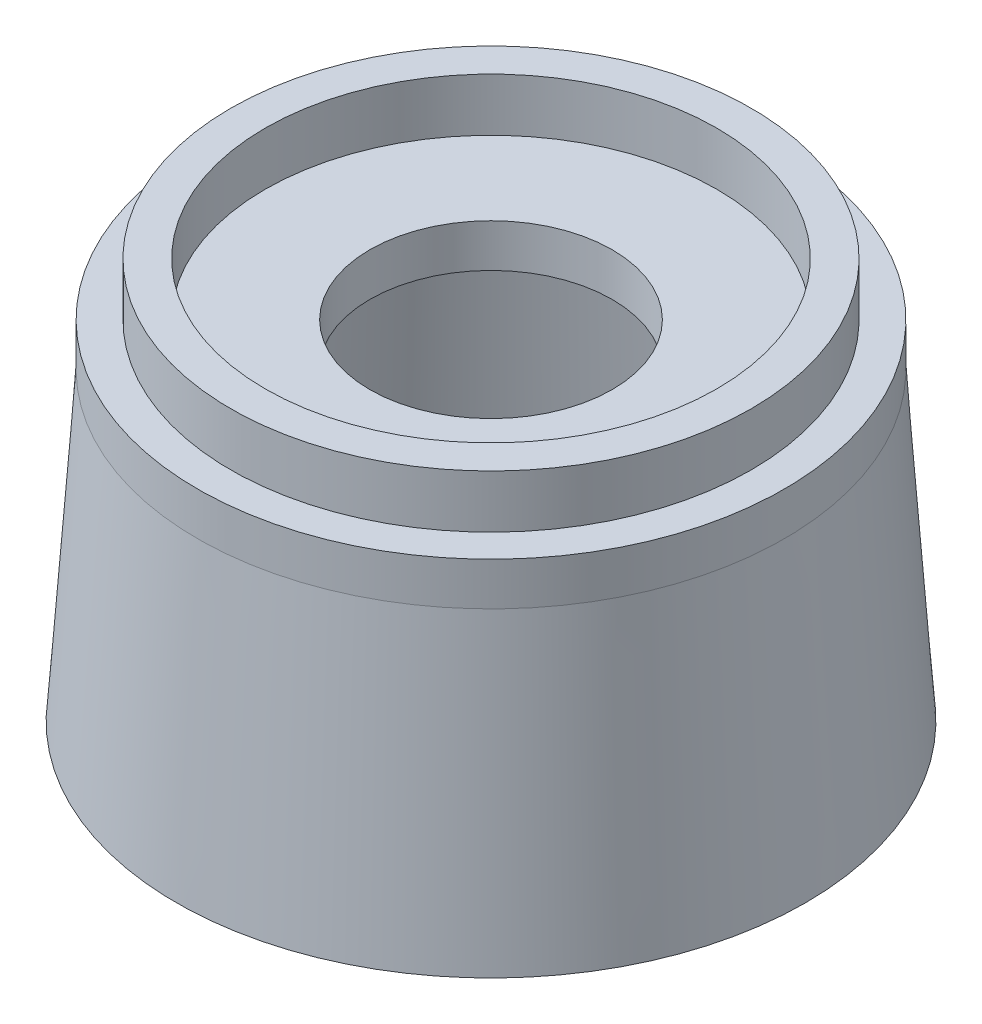
SolidWorks part; units mm, degrees
ref_plane "Plan de face" through (0, 0, 0) normal (0, 0, 1) x (1, 0, 0)
ref_plane "Plan de dessus" through (0, 0, 0) normal (0, 1, 0) x (1, 0, 0)
ref_plane "Plan de droite" through (0, 0, 0) normal (1, 0, 0) x (0, 0, -1)
sketch "Esquisse1" plane through (0, 0, 0) normal (0, 0, 1) x (1, 0, 0)
  line L0 (-11.4153, 52.3026) -> (-11.4153, -6.6974) construction
  line L1 (22.6847, 53.8026) -> (27.8847, 53.8026)
  line L2 (27.8847, 53.8026) -> (27.8847, 45.8026)
  line L3 (27.8847, 45.8026) -> (22.6847, 45.8026)
  line L4 (22.6847, 45.8026) -> (22.6847, 53.8026)
  line L5 (22.6847, 45.8026) -> (6.8847, 45.8026)
  line L6 (6.8847, 45.8026) -> (6.8847, 39.3026)
  line L7 (6.8847, 39.3026) -> (22.6847, 39.3026)
  line L8 (22.6847, 39.3026) -> (22.6847, 45.8026)
  line L9 (-11.4153, -6.6974) -> (36.0847, -6.6974) construction
  line L10 (22.6847, 45.8026) -> (32.8847, 45.8026)
  line L11 (22.6847, 45.8026) -> (22.6847, 39.3026)
  line L12 (22.6847, 39.3026) -> (32.8847, 39.3026)
  line L13 (32.8847, 45.8026) -> (32.8847, 39.3026)
  line L14 (32.8847, 39.3026) -> (36.0847, -6.6974)
  line L15 (29.8847, 39.3026) -> (33.3727, -6.6974)
  line L16 (36.0847, -6.6974) -> (33.3727, -6.6974)
  dimension "D1" = 59
  dimension "D2" = 39.3
  dimension "D3" = 8
  dimension "D4" = 21
  dimension "D5" = 5.2
  dimension "D6" = 15.8
  dimension "D7" = 6.5
  dimension "D8" = 26
  dimension "D9" = 47.5
  dimension "D10" = 46
  dimension "D11" = 3
revolve "Révolution1" add sketch "Esquisse1" angle 360 about L0
sketch "Esquisse2" plane through (0, 39.3026, 0) normal (0, -1, 0) x (1, 0, 0)
  line L1 (-10.1246, -42.549) -> (-12.1246, -42.549)
  line L2 (-10.1246, -42.549) -> (-10.1246, -40.049)
  line L3 (-10.1246, -40.049) -> (-12.1246, -40.049)
  line L4 (-12.1246, -42.549) -> (-12.1246, -40.049)
  line L5 (-10.1246, -42.549) -> (-12.1246, -40.049) construction
  line L6 (-10.1246, -40.049) -> (-12.1246, -42.549) construction
  circle A0 centre (-11.4153, 0) radius 41.3 construction
  point P0 (-11.1246, -41.299)
  point P7 (-12.9179, -43.4626)
  dimension "D1" = 2.5
  dimension "D2" = 2
extrude "Boss.-Extru.2" add sketch "Esquisse2" along normal blind 25
sketch "Esquisse3" plane through (0, 39.3026, 0) normal (0, -1, 0) x (1, 0, 0)
  line L0 (-11.1246, -42.549) -> (-11.7061, 41.299) construction
  line L1 (-12.1246, -42.549) -> (-10.1246, -42.549) construction
  line L2 (-11.7061, 41.299) -> (-11.4153, -0.625) construction
  line L3 (-11.4153, -0.625) -> (-52.7105, -0.625) construction
  line L5 (-53.9605, 0.375) -> (-51.4605, 0.375)
  line L6 (-53.9605, 0.375) -> (-53.9605, -1.625)
  line L7 (-53.9605, -1.625) -> (-51.4605, -1.625)
  line L8 (-51.4605, 0.375) -> (-51.4605, -1.625)
  line L9 (-53.9605, 0.375) -> (-51.4605, -1.625) construction
  line L10 (-53.9605, -1.625) -> (-51.4605, 0.375) construction
  line L11 (-12.7061, 42.549) -> (-10.7061, 42.549)
  line L12 (-12.7061, 42.549) -> (-12.7061, 40.049)
  line L13 (-12.7061, 40.049) -> (-10.7061, 40.049)
  line L14 (-10.7061, 42.549) -> (-10.7061, 40.049)
  line L15 (-12.7061, 42.549) -> (-10.7061, 40.049) construction
  line L16 (-12.7061, 40.049) -> (-10.7061, 42.549) construction
  arc A0 (-10.1246, -41.2798) -> (-12.1246, -41.2939) centre (-11.4153, 0) ccw construction
  dimension "D1" = 2
  dimension "D2" = 2.5
  dimension "D3" = 2
  dimension "D4" = 2.5
extrude "Boss.-Extru.3" add sketch "Esquisse3" along normal blind 25
